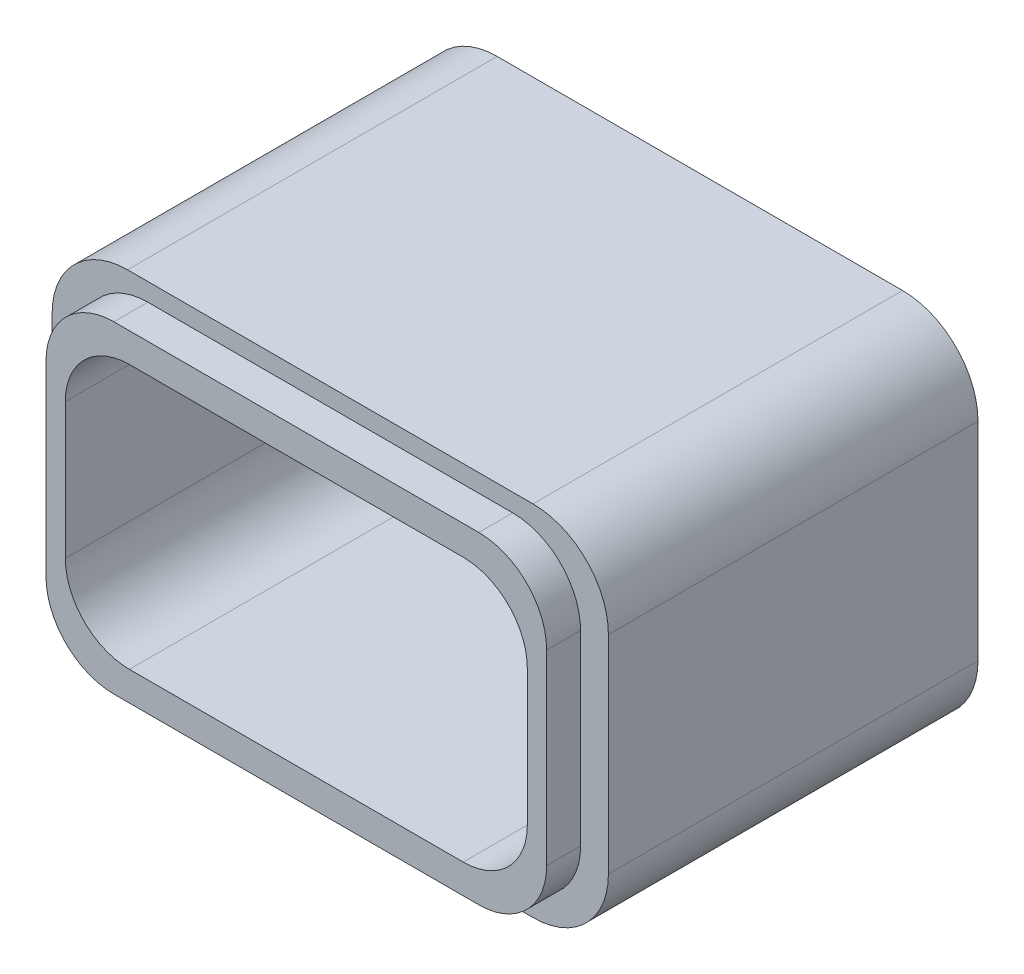
SolidWorks part; units mm, degrees
ref_plane "Front Plane" through (0, 0, 0) normal (0, 0, 1) x (1, 0, 0)
ref_plane "Top Plane" through (0, 0, 0) normal (0, 1, 0) x (1, 0, 0)
ref_plane "Right Plane" through (0, 0, 0) normal (1, 0, 0) x (0, 0, -1)
sketch "Sketch2" plane through (0, 0, 0) normal (0, 0, 1) x (1, 0, 0)
  line L1 (0, 0) -> (37.465, 0)
  line L2 (0, 0) -> (0, 24.13)
  line L3 (0, 24.13) -> (37.465, 24.13)
  line L4 (37.465, 0) -> (37.465, 24.13)
  dimension "D1" = 24.13
  dimension "D2" = 37.465
extrude "Boss-Extrude1" add sketch "Sketch2" along normal blind 24.892
sketch "Sketch3" plane through (0, 0, 24.892) normal (0, 0, 1) x (1, 0, 0)
  line L0 (37.465, 12.065) -> (34.29, 12.065)
  line L1 (37.465, 0) -> (37.465, 24.13) construction
  line L2 (18.7325, 24.13) -> (18.7325, 20.955)
  line L3 (37.465, 24.13) -> (0, 24.13) construction
  line L4 (0, 12.065) -> (3.175, 12.065)
  line L5 (0, 24.13) -> (0, 0) construction
  line L6 (18.7325, 0) -> (18.7325, 3.175)
  line L7 (0, 0) -> (37.465, 0) construction
  line L8 (3.175, 7.493) -> (3.175, 16.637)
  line L9 (7.493, 20.955) -> (29.972, 20.955)
  line L10 (34.29, 16.637) -> (34.29, 7.493)
  line L11 (29.972, 3.175) -> (7.493, 3.175)
  arc A0 (29.972, 20.955) -> (34.29, 16.637) centre (29.972, 16.637) cw
  arc A1 (34.29, 7.493) -> (29.972, 3.175) centre (29.972, 7.493) cw
  arc A2 (7.493, 3.175) -> (3.175, 7.493) centre (7.493, 7.493) cw
  arc A3 (3.175, 16.637) -> (7.493, 20.955) centre (7.493, 16.637) cw
  point P19 (3.175, 12.065)
  dimension "D5" = 4.318
  dimension "D1" = 3.175
  dimension "D2" = 3.175
  dimension "D3" = 3.175
  dimension "D4" = 3.175
extrude "Cut-Extrude1" cut sketch "Sketch3" against normal offset from surface (20.701 mm away) 4.191 contours A3 L8 A2 L11 A1 L10 A0 L9 up to face at (18.7325, 12.065, 0)
sketch "Sketch4" plane through (0, 0, 4.191) normal (0, 0, 1) x (1, 0, 0)
  line L5 (29.972, 3.175) -> (7.493, 3.175) construction
  line L7 (29.972, 3.175) -> (7.493, 3.175)
  line L8 (3.175, 16.637) -> (3.175, 7.493)
  line L9 (7.493, 3.175) -> (29.972, 3.175)
  line L10 (34.29, 7.493) -> (34.29, 16.637)
  line L11 (29.972, 20.955) -> (7.493, 20.955)
  line L12 (3.175, 16.637) -> (3.175, 7.493)
  line L13 (7.493, 3.175) -> (22.878, 3.175)
  line L15 (29.972, 20.955) -> (7.493, 20.955)
  line L16 (32.087, 8.5701) -> (32.0708, 10.8825)
  line L17 (27.4297, 15.4623) -> (21.5877, 15.4458)
  line L18 (16.931, 10.882) -> (16.9471, 8.5707)
  line L19 (21.5877, 3.9904) -> (27.4297, 4.0068)
  line L26 (19.0477, 16.2033) -> (29.9697, 16.2033)
  line L27 (34.1607, 12.0123) -> (34.1607, 7.4403)
  line L28 (19.0477, 3.2493) -> (29.9697, 3.2493)
  line L29 (14.8567, 12.0123) -> (14.8567, 7.4403)
  line L30 (24.5087, 16.2033) -> (24.5087, 3.2493) construction
  line L31 (14.8567, 9.7263) -> (34.1607, 9.7263) construction
  line L32 (16.9391, 9.7263) -> (32.0789, 9.7263) construction
  line L33 (24.5087, 15.4541) -> (24.5087, 3.9986) construction
  arc A4 (3.175, 7.493) -> (7.493, 3.175) centre (7.493, 7.493) ccw
  arc A5 (29.972, 3.175) -> (34.29, 7.493) centre (29.972, 7.493) ccw
  arc A6 (34.29, 16.637) -> (29.972, 20.955) centre (29.972, 16.637) ccw
  arc A7 (7.493, 20.955) -> (3.175, 16.637) centre (7.493, 16.637) ccw
  arc A8 (3.175, 7.493) -> (7.493, 3.175) centre (7.493, 7.493) ccw
  arc A10 (34.29, 16.637) -> (29.972, 20.955) centre (29.972, 16.637) ccw
  arc A11 (7.493, 20.955) -> (3.175, 16.637) centre (7.493, 16.637) ccw
  arc A14 (29.9697, 16.2033) -> (34.1607, 12.0123) centre (29.9697, 12.0123) cw
  arc A15 (29.9697, 3.2493) -> (34.1607, 7.4403) centre (29.9697, 7.4403) ccw
  arc A16 (14.8567, 7.4403) -> (19.0477, 3.2493) centre (19.0477, 7.4403) ccw
  arc A17 (19.0477, 16.2033) -> (14.8567, 12.0123) centre (19.0477, 12.0123) ccw
  spline S0 degree 2 poles (32.0708, 10.8825) (32.0732, 11.0351) (32.0535, 11.3845) (31.9835, 11.899) (31.6903, 12.8915) (30.7816, 14.2408) (29.419, 15.1192) (28.4147, 15.3932) (27.9094, 15.4522) (27.5548, 15.4648) (27.4297, 15.4623) knots 0 0 0 0.046875 0.09375 0.1875 0.375 0.625 0.8125 0.90625 0.953125 1 1 1
  spline S1 degree 2 poles (21.5877, 15.4458) (21.4628, 15.4487) (21.1067, 15.4373) (20.5958, 15.379) (19.5917, 15.1071) (18.2257, 14.2298) (17.3162, 12.886) (17.02, 11.8893) (16.9499, 11.3822) (16.9291, 11.0348) (16.931, 10.882) knots 0 0 0 0.046875 0.09375 0.1875 0.375 0.625 0.8125 0.90625 0.953125 1 1 1
  spline S2 degree 2 poles (16.9471, 8.5707) (16.9447, 8.4181) (16.9644, 8.0687) (17.0343, 7.5542) (17.3274, 6.5617) (18.2359, 5.2123) (19.5984, 4.3337) (20.6027, 4.0596) (21.108, 4.0005) (21.4626, 3.9879) (21.5877, 3.9904) knots 0 0 0 0.046875 0.09375 0.1875 0.375 0.625 0.8125 0.90625 0.953125 1 1 1
  spline S3 degree 2 poles (27.4297, 4.0068) (27.5546, 4.0039) (27.9107, 4.0153) (28.4216, 4.0736) (29.4258, 4.3454) (30.7919, 5.2225) (31.7015, 6.5662) (31.9978, 7.5629) (32.068, 8.07) (32.0888, 8.4173) (32.087, 8.5701) knots 0 0 0 0.046875 0.09375 0.1875 0.375 0.625 0.8125 0.90625 0.953125 1 1 1
  dimension "D2" = 10.922
  dimension "D3" = 5.842
  dimension "D4" = 4.572
  dimension "D5" = 10.922
  dimension "D6" = 2.3114
  dimension "D7" = 5.842
  dimension "D8" = 15.1395
  dimension "D9" = 19.304
  dimension "D10" = 12.954
  dimension "D11" = 11.4554
  dimension "D1" = 0
extrude "Cut-Extrude3" cut sketch "Sketch4" against normal blind 4.191
sketch "Sketch5" plane through (0, 0, 4.191) normal (0, 0, 1) x (1, 0, 0)
  line L0 (24.5087, 15.4541) -> (15.3229, 15.4541) construction
  line L1 (27.4297, 15.4623) -> (21.5877, 15.4458) construction
  line L2 (3.175, 7.493) -> (3.175, 16.637) construction
  line L3 (7.0679, 19.3698) -> (7.0679, 3.7996)
  line L13 (7.0679, 15.4541) -> (3.175, 15.4541) construction
  line L14 (15.3229, 3.7996) -> (7.0679, 3.7996)
  line L15 (7.0679, 19.3698) -> (15.3229, 19.3698)
  line L16 (15.3229, 19.3698) -> (15.3229, 3.7996)
  line L17 (11.1954, 19.3698) -> (11.1954, 3.7996) construction
  circle A0 centre (11.1954, 11.5847) radius 1.27
  point P9 (11.1954, 8.8218)
  dimension "D2" = 2.54
  dimension "D1" = 8.255
  dimension "D3" = 15.5702
fillet "Fillet1" radius 5.08 4 edges at (37.465, 24.13, 12.446) (37.465, 0, 12.446) (0, 0, 12.446) (0, 24.13, 12.446)
sketch "Sketch7" plane through (0, 0, 24.892) normal (0, 0, 1) x (1, 0, 0)
  line L0 (7.493, 20.955) -> (29.972, 20.955) construction
  line L1 (34.29, 16.637) -> (34.29, 7.493) construction
  line L2 (29.972, 3.175) -> (7.493, 3.175) construction
  line L3 (3.175, 7.493) -> (3.175, 16.637) construction
  line L4 (7.493, 20.955) -> (29.972, 20.955)
  line L5 (34.29, 16.637) -> (34.29, 7.493)
  line L6 (29.972, 3.175) -> (7.493, 3.175)
  line L7 (3.175, 7.493) -> (3.175, 16.637)
  line L8 (18.7325, 24.13) -> (18.7325, 0) construction
  line L9 (0, 12.065) -> (37.465, 12.065) construction
  line L12 (37.465, 5.08) -> (37.465, 19.05)
  line L13 (32.385, 24.13) -> (5.08, 24.13)
  line L14 (0, 19.05) -> (0, 5.08)
  line L15 (5.08, 0) -> (32.385, 0)
  line L16 (37.465, 5.08) -> (37.465, 19.05)
  line L17 (32.385, 24.13) -> (5.08, 24.13)
  line L18 (0, 19.05) -> (0, 5.08)
  line L19 (5.08, 0) -> (32.385, 0)
  line L22 (6.4452, 1.2065) -> (31.0197, 1.2065)
  line L23 (35.5917, 5.7785) -> (35.5917, 18.3515)
  line L24 (31.0197, 22.9235) -> (6.4453, 22.9235)
  line L25 (1.8732, 18.3515) -> (1.8732, 5.7785)
  arc A0 (34.29, 16.637) -> (29.972, 20.955) centre (29.972, 16.637) ccw construction
  arc A1 (29.972, 3.175) -> (34.29, 7.493) centre (29.972, 7.493) ccw construction
  arc A2 (3.175, 7.493) -> (7.493, 3.175) centre (7.493, 7.493) ccw construction
  arc A3 (7.493, 20.955) -> (3.175, 16.637) centre (7.493, 16.637) ccw construction
  arc A4 (34.29, 16.637) -> (29.972, 20.955) centre (29.972, 16.637) ccw
  arc A5 (29.972, 3.175) -> (34.29, 7.493) centre (29.972, 7.493) ccw
  arc A6 (3.175, 7.493) -> (7.493, 3.175) centre (7.493, 7.493) ccw
  arc A7 (7.493, 20.955) -> (3.175, 16.637) centre (7.493, 16.637) ccw
  arc A12 (37.465, 19.05) -> (32.385, 24.13) centre (32.385, 19.05) ccw
  arc A13 (5.08, 24.13) -> (0, 19.05) centre (5.08, 19.05) ccw
  arc A14 (0, 5.08) -> (5.08, 0) centre (5.08, 5.08) ccw
  arc A15 (32.385, 0) -> (37.465, 5.08) centre (32.385, 5.08) ccw
  arc A16 (37.465, 19.05) -> (32.385, 24.13) centre (32.385, 19.05) ccw
  arc A17 (5.08, 24.13) -> (0, 19.05) centre (5.08, 19.05) ccw
  arc A18 (0, 5.08) -> (5.08, 0) centre (5.08, 5.08) ccw
  arc A19 (32.385, 0) -> (37.465, 5.08) centre (32.385, 5.08) ccw
  arc A20 (6.4453, 22.9235) -> (1.8732, 18.3515) centre (6.4453, 18.3515) ccw
  arc A21 (1.8732, 5.7785) -> (6.4452, 1.2065) centre (6.4453, 5.7785) ccw
  arc A22 (35.5917, 18.3515) -> (31.0197, 22.9235) centre (31.0197, 18.3515) ccw
  arc A23 (31.0197, 1.2065) -> (35.5917, 5.7785) centre (31.0197, 5.7785) ccw
  dimension "D1" = 0
extrude "Boss-Extrude3" add sketch "Sketch7" along normal blind 2.286 contours L22 A23 L23 A22 L24 A20 L25 A21 L13 L0 L1 L2 L3 L8 L9 L12
sketch "Sketch8" plane through (0, 0, 0) normal (-1, 0, 0) x (0, 0, 1)
  line L0 (0, 12.065) -> (24.892, 12.065) construction
  line L1 (0, 19.05) -> (0, 5.08) construction
  line L2 (24.892, 18.3515) -> (24.892, 5.7785) construction
  circle A0 centre (12.446, 12.065) radius 1.905
  dimension "D1" = 3.81
extrude "Cut-Extrude4" cut sketch "Sketch8" against normal blind 7.62
